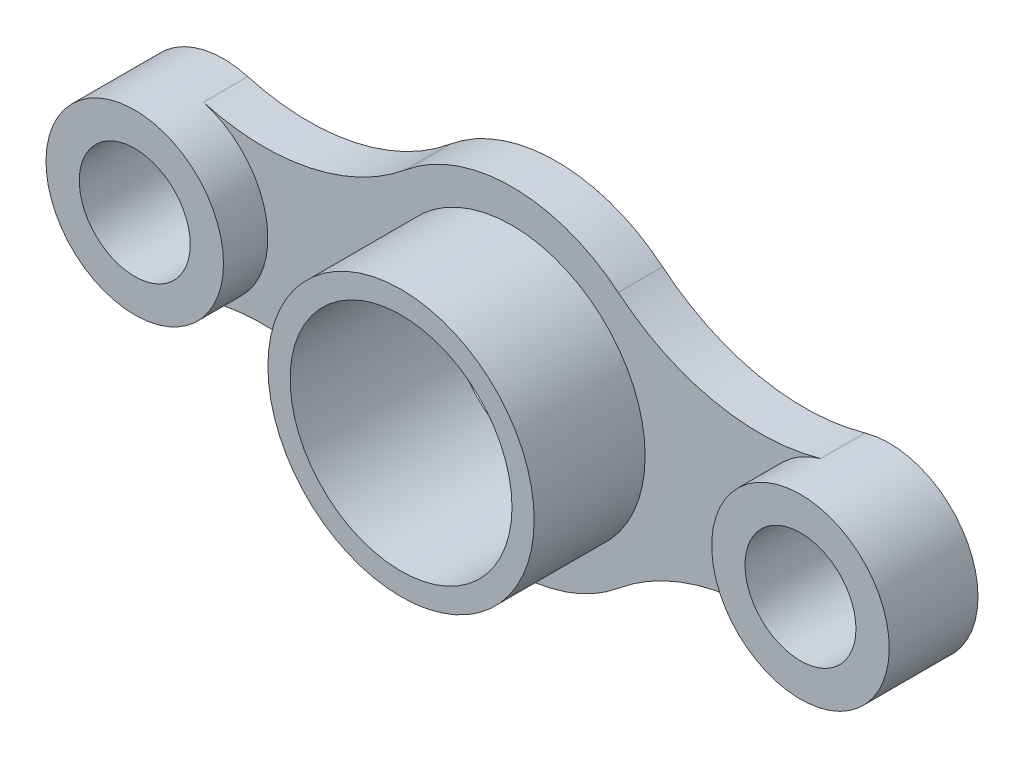
SolidWorks part; units mm, degrees
ref_plane "Front Plane" through (0, 0, 0) normal (0, 0, 1) x (1, 0, 0)
ref_plane "Top Plane" through (0, 0, 0) normal (0, 1, 0) x (1, 0, 0)
ref_plane "Right Plane" through (0, 0, 0) normal (1, 0, 0) x (0, 0, -1)
sketch "Sketch1" plane through (0, 0, 0) normal (0, 0, 1) x (1, 0, 0)
  arc A0 (-47.8929, -57.7172) -> (47.8929, -57.7172) centre (0, 0) ccw
  arc A1 (139.0714, -38.4781) -> (139.0714, 38.4781) centre (150, 0) ccw
  arc A2 (-139.0714, 38.4781) -> (-139.0714, -38.4781) centre (-150, 0) ccw
  arc A3 (-139.0714, -38.4781) -> (-47.8929, -57.7172) centre (-111.75, -134.6734) cw
  arc A4 (-139.0714, 38.4781) -> (-47.8929, 57.7172) centre (-111.75, 134.6734) ccw
  arc A5 (139.0714, 38.4781) -> (47.8929, 57.7172) centre (111.75, 134.6734) cw
  arc A6 (139.0714, -38.4781) -> (47.8929, -57.7172) centre (111.75, -134.6734) ccw
  arc A7 (47.8929, 57.7172) -> (-47.8929, 57.7172) centre (0, 0) ccw
  point P19 (-111.7537, 134.6689)
  dimension "D1" = 150
  dimension "D2" = 80
  dimension "D3" = 80
  dimension "D6" = 100
  dimension "D4" = 150
  dimension "D5" = 150
extrude "Boss-Extrude1" add sketch "Sketch1" along normal blind 20
sketch "Sketch3" plane through (0, 0, 20) normal (0, 0, 1) x (1, 0, 0)
  circle A0 centre (-150, 0) radius 40
  circle A1 centre (150, 0) radius 40
  dimension "D1" = 80
  dimension "D2" = 80
extrude "Boss-Extrude2" add sketch "Sketch3" along normal blind 20
sketch "Sketch4" plane through (0, 0, 20) normal (0, 0, 1) x (1, 0, 0)
  circle A0 centre (0, 0) radius 60
  dimension "D1" = 120
extrude "Boss-Extrude3" add sketch "Sketch4" along normal blind 50
sketch "Sketch5" plane through (0, 0, 20) normal (0, 0, 1) x (1, 0, 0)
  circle A0 centre (0, 0) radius 50
  circle A1 centre (-150, 0) radius 25
  circle A2 centre (150, 0) radius 25
  dimension "D1" = 100
  dimension "D2" = 50
  dimension "D3" = 50
extrude "Cut-Extrude1" cut sketch "Sketch5" against normal through all both and the other way through all
